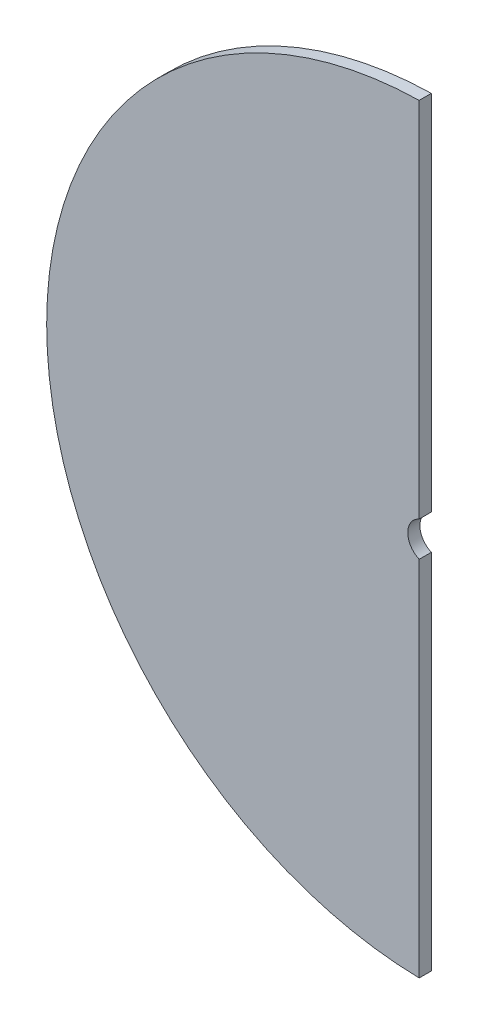
SolidWorks part; units mm, degrees
ref_plane "Ebene vorne" through (0, 0, 0) normal (0, 0, 1) x (1, 0, 0)
ref_plane "Ebene oben" through (0, 0, 0) normal (0, 1, 0) x (1, 0, 0)
ref_plane "Ebene rechts" through (0, 0, 0) normal (1, 0, 0) x (0, 0, -1)
sketch "Skizze1" plane through (0, 0, 0) normal (0, 0, 1) x (1, 0, 0)
  line L0 (0, 50) -> (0, 2.5)
  line L1 (0, -2.5) -> (0, -50)
  line L2 (0, 2.5) -> (0, -2.5) construction
  arc A0 (0, 50) -> (0, -50) centre (0, 0) ccw
  arc A1 (0, 2.5) -> (0, -2.5) centre (0, 0) ccw
  point P6 (0, 0)
  dimension "D1" = 2.5
  dimension "D2" = 50
extrude "Aufsatz-Linear austragen1" add sketch "Skizze1" along normal blind 1.6
sketch "Skizze2" plane through (0, 0, 1.6) normal (0, 0, 1) x (1, 0, 0)
  line L0 (-1, 49.99) -> (-1, -49.99)
  line L1 (-1, 49.99) -> (12.9253, 54.3018)
  line L2 (12.9253, 54.3018) -> (10.8689, -55.9665)
  line L3 (10.8689, -55.9665) -> (-1, -49.99)
  line L4 (0, 2.5) -> (0, 50) construction
  arc A0 (0, 50) -> (0, -50) centre (0, 0) ccw construction
  dimension "D1" = 1
extrude "Schnitt-Linear austragen1" cut sketch "Skizze2" against normal through all
sketch "Skizze3" plane through (0, 0, 1.6) normal (0, 0, 1) x (1, 0, 0)
  line L0 (-3.7329, 49.8605) -> (-3.7329, 53.7833)
  line L1 (-3.7329, 53.7833) -> (-1.076, 53.7833)
  line L2 (-1.076, 53.7833) -> (-1, 49.99)
  line L3 (-1, 49.99) -> (-1, 48.4127)
  line L4 (-1, 49.99) -> (-1, 2.2913) construction
  line L5 (-1, 48.4127) -> (-3.7329, 48.4127)
  line L6 (-3.7329, 48.4127) -> (-3.7329, 49.8605)
  arc A0 (-1, 49.99) -> (-1, -49.99) centre (0, 0) ccw construction
extrude "Aufsatz-Linear austragen2" [suppressed] add sketch "Skizze3" against normal blind 1.6
